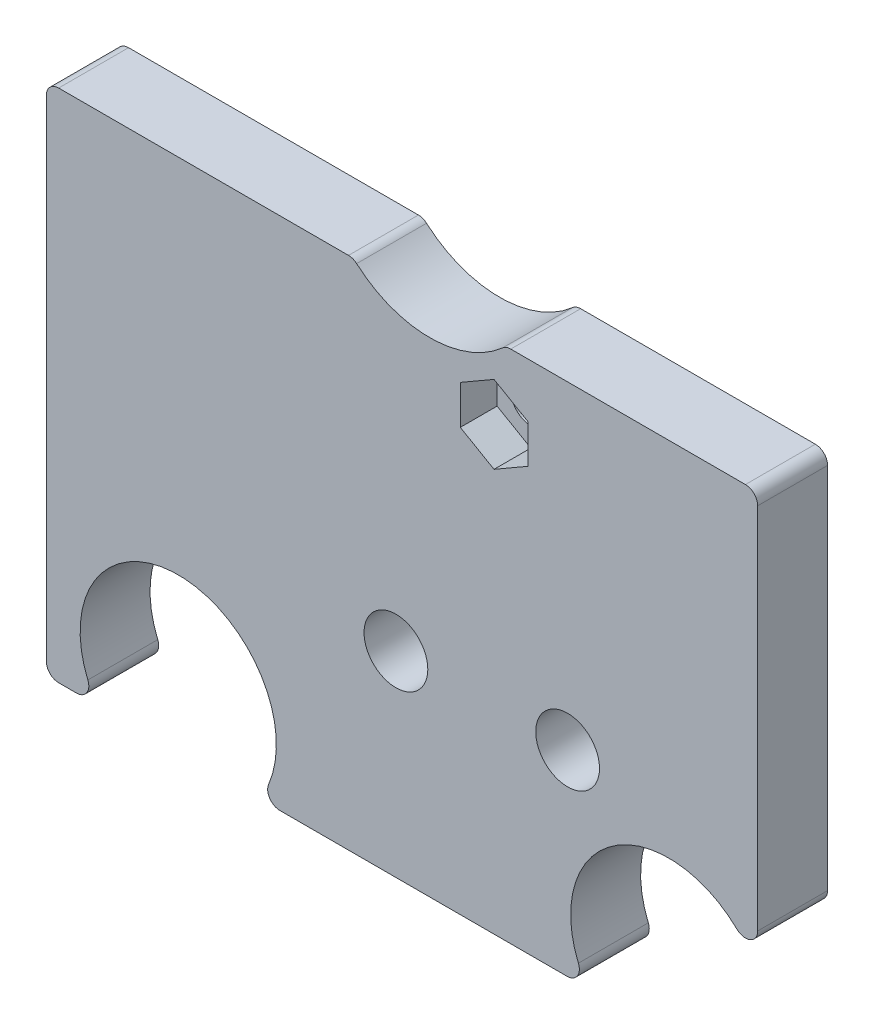
SolidWorks part; units mm, degrees
ref_plane "Ebene vorne" through (0, 0, 0) normal (0, 0, 1) x (1, 0, 0)
ref_plane "Ebene oben" through (0, 0, 0) normal (0, 1, 0) x (1, 0, 0)
ref_plane "Ebene rechts" through (0, 0, 0) normal (1, 0, 0) x (0, 0, -1)
sketch "Skizze1" plane through (0, 0, 0) normal (0, 0, 1) x (1, 0, 0)
  line L0 (-2.75, -32.5) -> (11.25, -32.5) construction
  line L1 (-20.5, -44) -> (19.5, -44) construction
  line L2 (4.25, -32.5) -> (4.25, 11.0626) construction
  circle A1 centre (0, 0) radius 9
  circle A2 centre (-20.5, -44) radius 8
  circle A3 centre (19.5, -44) radius 8
  circle A5 centre (11.25, -32.5) radius 2.6
  circle A7 centre (-2.75, -32.5) radius 2.6
  dimension "D6" = 8
  dimension "D7" = 16
  dimension "D8" = 18
  dimension "D9" = 5.2
  dimension "D10" = 5.2
  dimension "D2" = 40
  dimension "D3" = 11.5
  dimension "D4" = 14
  dimension "D5" = 44
  dimension "D11" = 19.5
  dimension "D13" = 8.25
sketch "Skizze2" plane through (0, 0, 0) normal (0, 0, 1) x (1, 0, 0)
  line L1 (-31.25, -6.5) -> (26.75, -6.5)
  line L2 (-31.25, -6.5) -> (-31.25, -48.5)
  line L3 (-31.25, -48.5) -> (26.75, -48.5)
  line L4 (26.75, -6.5) -> (26.75, -48.5)
  line L5 (-31.25, -6.5) -> (26.75, -48.5) construction
  line L6 (-31.25, -48.5) -> (26.75, -6.5) construction
  line L7 (-2.75, -32.5) -> (11.25, -32.5) construction
  line L8 (4.25, -32.5) -> (4.25, 11.0626) construction
  point P0 (-2.25, -27.5)
  dimension "D1" = 5
  dimension "D2" = 35.5
  dimension "D3" = 42
  dimension "D4" = 22.5
extrude "Aufsatz-Linear austragen1" add sketch "Skizze2" along normal blind 5.7
extrude "Schnitt-Linear austragen2" cut sketch "Skizze1" along normal through all
sketch "Skizze3" plane through (0, 0, 5.7) normal (0, 0, 1) x (1, 0, 0)
  line L2 (26.75, -48.5) -> (26.75, -47.3819)
  line L3 (26.1144, -48.5) -> (26.75, -48.5)
  line L4 (26.75, -48.5) -> (26.75, -47.3819)
  line L5 (26.1144, -48.5) -> (26.75, -48.5)
  arc A1 (26.1144, -48.5) -> (26.75, -47.3819) centre (19.5, -44) ccw
  arc A2 (26.1144, -48.5) -> (26.75, -47.3819) centre (19.5, -44) ccw
  dimension "D1" = 0
extrude "Schnitt-Linear austragen3" cut sketch "Skizze3" against normal through all
fillet "Verrundung1" radius 1 9 edges at (26.75, -6.5, 2.85) (-6.2249, -6.5, 2.85) (6.2249, -6.5, 2.85) (26.75, -40.6181, 2.85) (12.8856, -48.5, 2.85) (-13.8856, -48.5, 2.85) (-27.1144, -48.5, 2.85) (-31.25, -6.5, 2.85) (-31.25, -48.5, 2.85)
sketch "Skizze4" plane through (0, 0, 5.7) normal (0, 0, 1) x (1, 0, 0)
  line L1 (2.5, -14.0877) -> (5.25, -15.6754)
  line L2 (5.25, -15.6754) -> (8, -14.0877)
  line L3 (8, -14.0877) -> (8, -10.9123)
  line L4 (8, -10.9123) -> (5.25, -9.3246)
  line L5 (5.25, -9.3246) -> (2.5, -10.9123)
  line L6 (2.5, -10.9123) -> (2.5, -14.0877)
  circle A0 centre (5.25, -12.5) radius 2.75 construction
  circle A1 centre (11.25, -32.5) radius 2.6 construction
  dimension "D1" = 5.5
  dimension "D2" = 20
  dimension "D3" = 6
extrude "Schnitt-Linear austragen4" cut sketch "Skizze4" against normal blind 3
sketch "Skizze5" plane through (0, 0, 2.7) normal (0, 0, 1) x (1, 0, 0)
  circle A0 centre (5.25, -12.5) radius 1.6
  dimension "D1" = 3.2
extrude "Schnitt-Linear austragen5" cut sketch "Skizze5" against normal through all
